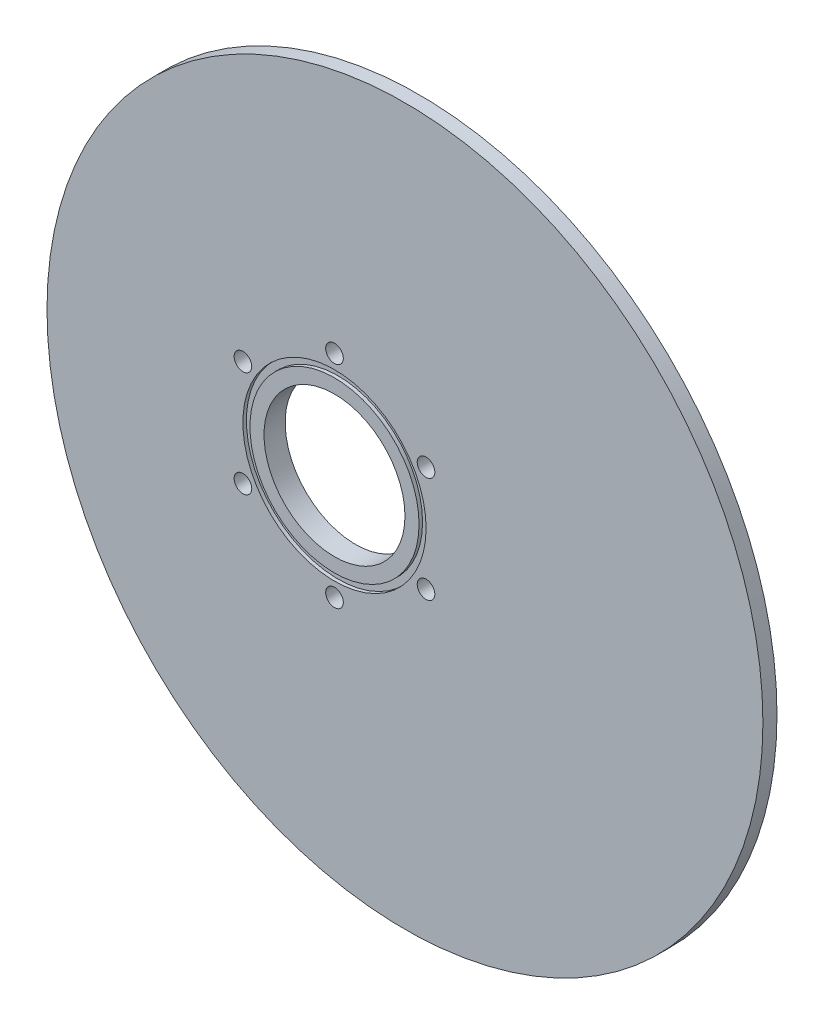
SolidWorks part; units mm, degrees
ref_plane "Front Plane" through (0, 0, 0) normal (0, 0, 1) x (1, 0, 0)
ref_plane "Top Plane" through (0, 0, 0) normal (0, 1, 0) x (1, 0, 0)
ref_plane "Right Plane" through (0, 0, 0) normal (1, 0, 0) x (0, 0, -1)
sketch "Sketch2" plane through (0, 0, 0) normal (1, 0, 0) x (0, 0, -1)
  line L0 (0, 0) -> (0, 101.6)
  line L1 (0, 111.265) -> (0, -111.265) construction
  line L2 (0, 101.6) -> (4, 101.6)
  line L3 (4, 101.6) -> (4, 95.25)
  line L4 (4, 95.25) -> (6, 95.25)
  line L5 (6, 95.25) -> (6, 0)
  line L6 (3.3, 0) -> (-3.3, 0) construction
  line L7 (6, 0) -> (0, 0)
  dimension "D1" = 101.6
  dimension "D2" = 6
  dimension "D3" = 4
  dimension "D4" = 6.35
revolve "Revolve1" add sketch "Sketch2" angle 360 about L7
sketch "Sketch3" plane through (0, 0, 0) normal (0, 0, 1) x (1, 0, 0)
  line L1 (0, -3.3) -> (0, 3.3) construction
  circle A0 centre (-20, 0) radius 20
  dimension "D1" = 40
  dimension "D2" = 20
extrude "Cut-Extrude1" cut sketch "Sketch3" against normal through all
sketch "Sketch4" plane through (0, 0, 0) normal (0, 0, 1) x (1, 0, 0)
  circle A0 centre (-20, 0) radius 30 construction
  circle A1 centre (-20, 30) radius 2.5
  circle A2 centre (5.9808, 15) radius 2.5
  circle A3 centre (5.9808, -15) radius 2.5
  circle A4 centre (-20, -30) radius 2.5
  circle A5 centre (-45.9808, -15) radius 2.5
  circle A6 centre (-45.9808, 15) radius 2.5
  point P18 (-20, 0)
  dimension "D1" = 60
  dimension "D2" = 5
  dimension "D3" = 6
extrude "Cut-Extrude3" cut sketch "Sketch4" against normal through all
sketch "Sketch5" plane through (0, 0, 0) normal (0, 0, 1) x (1, 0, 0)
  circle A0 centre (-20, 0) radius 24
  circle A1 centre (-20, 0) radius 26
  circle A2 centre (-20, 0) radius 25 construction
  dimension "D1" = 2
  dimension "D2" = 1
  dimension "D3" = 50
extrude "Cut-Extrude4" cut sketch "Sketch5" against normal blind 1
